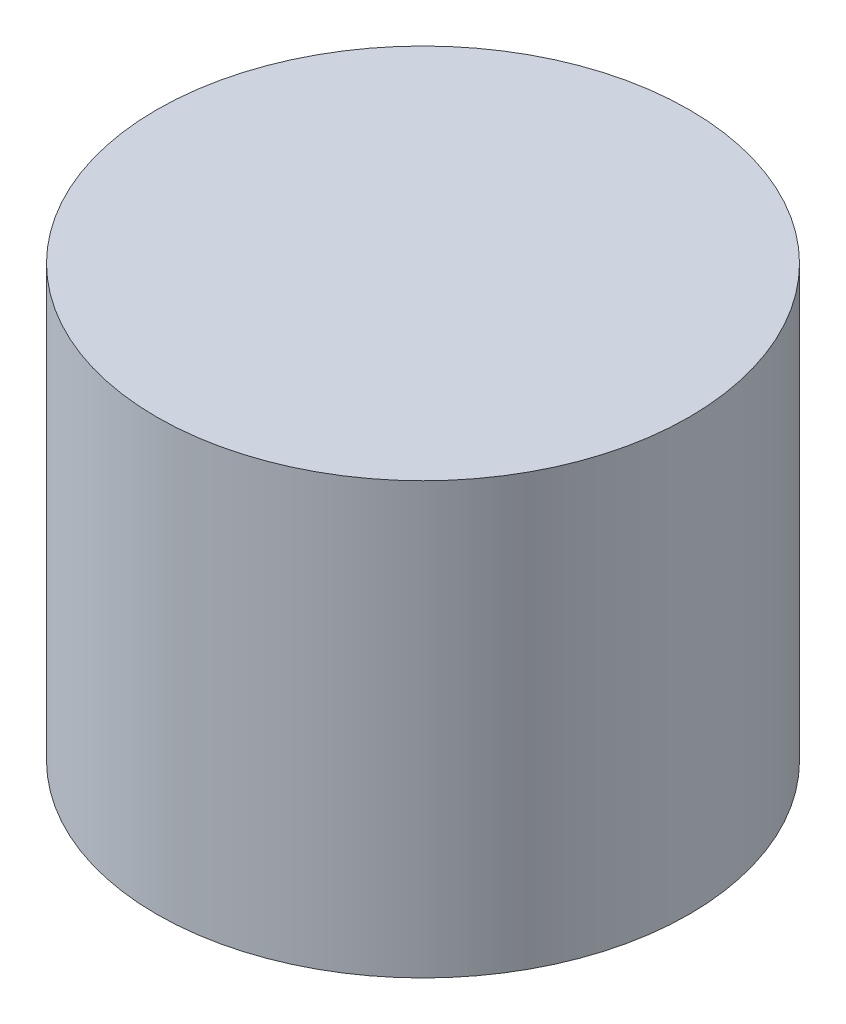
SolidWorks part; units mm, degrees
ref_plane "Front Plane" through (0, 0, 0) normal (0, 0, 1) x (1, 0, 0)
ref_plane "Top Plane" through (0, 0, 0) normal (0, 1, 0) x (1, 0, 0)
ref_plane "Right Plane" through (0, 0, 0) normal (1, 0, 0) x (0, 0, -1)
sketch "Sketch2" plane through (0, 0, 0) normal (0, 1, 0) x (1, 0, 0)
  circle A0 centre (0, 0) radius 11.5
extrude "Boss-Extrude1" add sketch "Sketch2" against normal blind 18.6
